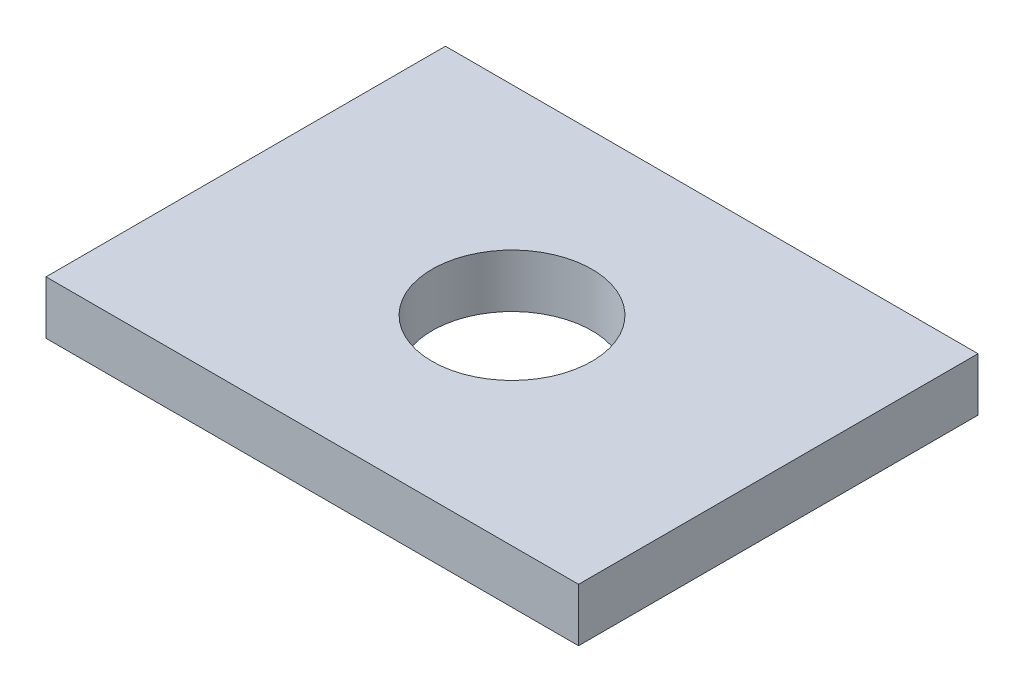
SolidWorks part; units mm, degrees
ref_plane "Front Plane" through (0, 0, 0) normal (0, 0, 1) x (1, 0, 0)
ref_plane "Top Plane" through (0, 0, 0) normal (0, 1, 0) x (1, 0, 0)
ref_plane "Right Plane" through (0, 0, 0) normal (1, 0, 0) x (0, 0, -1)
sketch "Sketch1" plane through (0, 0, 0) normal (0, 1, 0) x (1, 0, 0)
  line L1 (-12.7, -9.525) -> (12.7, -9.525)
  line L2 (-12.7, -9.525) -> (-12.7, 9.525)
  line L3 (-12.7, 9.525) -> (12.7, 9.525)
  line L4 (12.7, -9.525) -> (12.7, 9.525)
  line L5 (-12.7, -9.525) -> (12.7, 9.525) construction
  line L6 (-12.7, 9.525) -> (12.7, -9.525) construction
  point P0 (0, 0)
  dimension "D1" = 25.4
  dimension "D2" = 19.05
extrude "Boss-Extrude1" add sketch "Sketch1" along normal blind 2.54
sketch "Sketch2" plane through (0, 2.54, 0) normal (0, 1, 0) x (1, 0, 0)
  circle A0 centre (0, 0) radius 3.81
  dimension "D1" = 7.62
extrude "Cut-Extrude1" cut sketch "Sketch2" against normal through all
